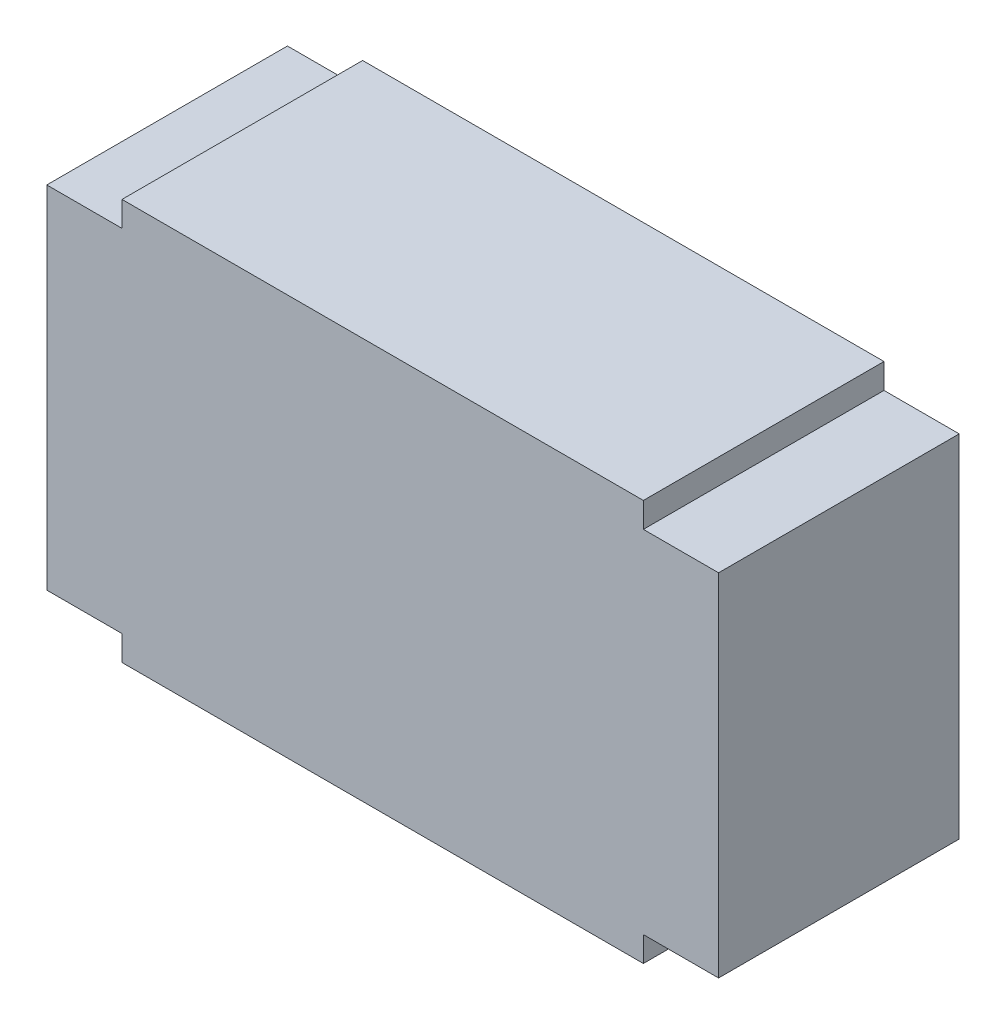
SolidWorks part; units mm, degrees
ref_plane "前视基准面" through (0, 0, 0) normal (0, 0, 1) x (1, 0, 0)
ref_plane "上视基准面" through (0, 0, 0) normal (0, 1, 0) x (1, 0, 0)
ref_plane "右视基准面" through (0, 0, 0) normal (1, 0, 0) x (0, 0, -1)
sketch "草图1" plane through (0, 0, 0) normal (0, 0, 1) x (1, 0, 0)
  line L0 (-1.3, -1) -> (-1.3, -0.875)
  line L1 (-1.3, -0.875) -> (-1.675, -0.875)
  line L2 (-1.675, -0.875) -> (-1.675, 0.875)
  line L3 (-1.675, 0.875) -> (-1.3, 0.875)
  line L4 (-1.3, 0.875) -> (-1.3, 1)
  line L5 (-1.3, 1) -> (1.3, 1)
  line L6 (1.3, 1) -> (1.3, 0.875)
  line L7 (1.3, 0.875) -> (1.675, 0.875)
  line L8 (1.675, 0.875) -> (1.675, -0.875)
  line L9 (1.675, -0.875) -> (1.3, -0.875)
  line L10 (1.3, -0.875) -> (1.3, -1)
  line L11 (1.3, -1) -> (-1.3, -1)
extrude "Component_Outline" add sketch "草图1" along normal blind 1.2 separate body
sketch3d "3D草图1"
  line L0 (0, 0, 0) -> (1, 0, 0)
  line L1 (0, 0, 0) -> (0, 1, 0)
  line L2 (0, 0, 0) -> (0, 0, 1)
  point P0 (0, 0, 0)
